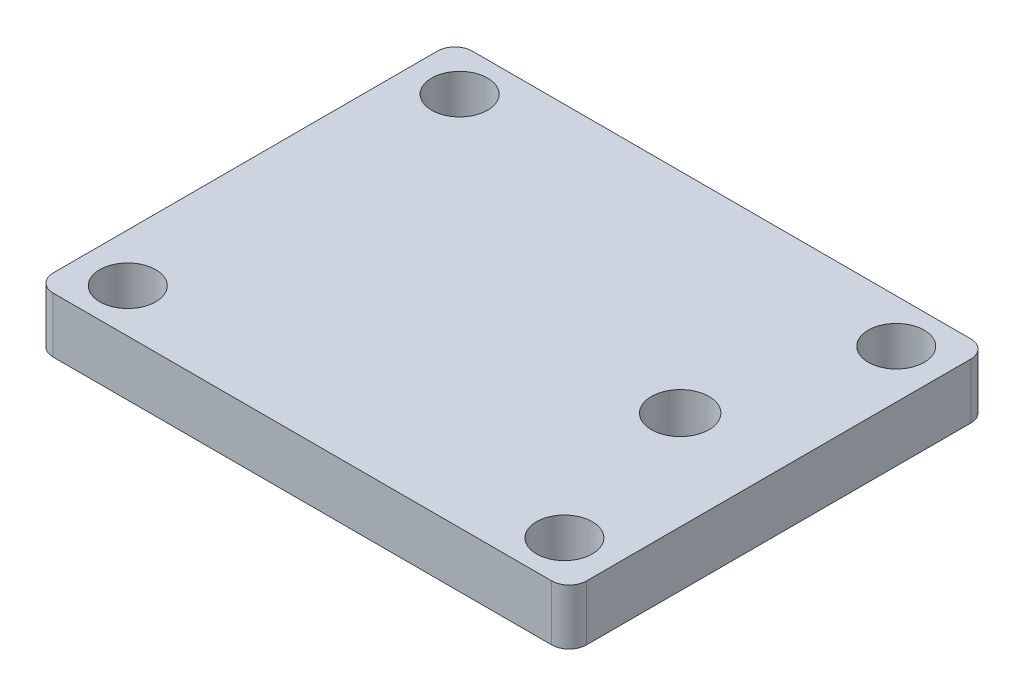
SolidWorks part; units mm, degrees
ref_plane "Front Plane" through (0, 0, 0) normal (0, 0, 1) x (1, 0, 0)
ref_plane "Top Plane" through (0, 0, 0) normal (0, 1, 0) x (1, 0, 0)
ref_plane "Right Plane" through (0, 0, 0) normal (1, 0, 0) x (0, 0, -1)
sketch "Sketch1" plane through (0, 0, 0) normal (0, 1, 0) x (1, 0, 0)
  line L1 (-15.27, -12) -> (15.27, -12)
  line L2 (-15.27, -12) -> (-15.27, 12)
  line L3 (-15.27, 12) -> (15.27, 12)
  line L4 (15.27, -12) -> (15.27, 12)
  line L5 (-15.27, -12) -> (15.27, 12) construction
  line L6 (-15.27, 12) -> (15.27, -12) construction
  circle A0 centre (-12.5, 9.5) radius 1.6
  circle A1 centre (-12.5, -9.5) radius 1.6
  circle A2 centre (12.5, -9.5) radius 1.6
  circle A3 centre (12.5, 9.5) radius 1.6
  point P0 (0, 0)
  point P14 (0, 0)
  point P15 (0, 0)
  point P16 (0, 0)
  point P17 (0, 0)
  point P18 (0, 0)
  point P19 (12.0289, 10.3831)
  point P20 (0, 0)
  dimension "D3" = 3.2
  dimension "D1" = 30.54
  dimension "D2" = 24
  dimension "D4" = 25
  dimension "D5" = 19
  dimension "D6" = 12.5
  dimension "D7" = 9.5
extrude "Boss-Extrude1" add sketch "Sketch1" along normal blind 3.175
fillet "Fillet1" radius 1 4 edges at (15.27, 1.5875, -12) (15.27, 1.5875, 12) (-15.27, 1.5875, 12) (-15.27, 1.5875, -12)
sketch "Sketch3" plane through (0, 3.175, 0) normal (0, 1, 0) x (1, 0, 0)
  line L0 (15.27, -11) -> (15.27, 11) construction
  circle A3 centre (9.63, 0) radius 1.65
  point P5 (0, 0)
  dimension "D1" = 5.64
  dimension "D2" = 3.3
extrude "Cut-Extrude1" cut sketch "Sketch3" against normal up to next
equation "\"D6@Sketch1\"=\"D4@Sketch1\"/2"
equation "\"D7@Sketch1\"=\"D5@Sketch1\"/2"
